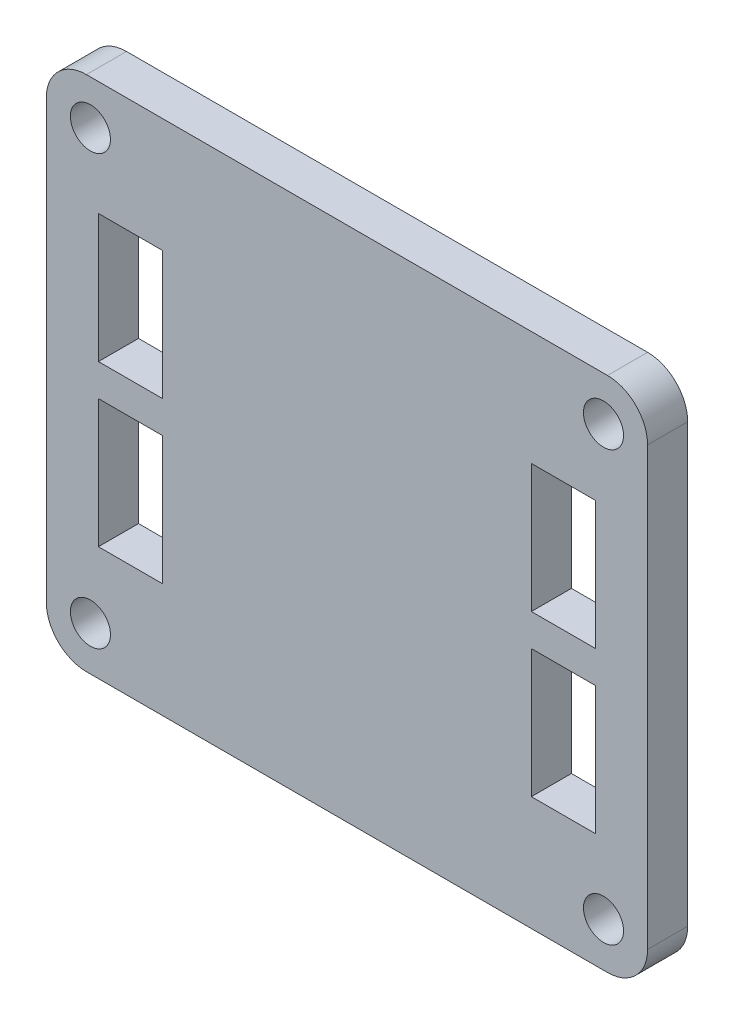
SolidWorks part; units mm, degrees
ref_plane "前基準面" through (0, 0, 0) normal (0, 0, 1) x (1, 0, 0)
ref_plane "上基準面" through (0, 0, 0) normal (0, 1, 0) x (1, 0, 0)
ref_plane "右基準面" through (0, 0, 0) normal (1, 0, 0) x (0, 0, -1)
sketch "草圖1" plane through (0, 0, 0) normal (0, 0, 1) x (1, 0, 0)
  line L1 (37.5, -32.25) -> (-37.5, -32.25)
  line L2 (37.5, -32.25) -> (37.5, 32.25)
  line L3 (37.5, 32.25) -> (-37.5, 32.25)
  line L4 (-37.5, -32.25) -> (-37.5, 32.25)
  line L5 (0, 32.25) -> (0, -32.25) construction
  line L6 (37.5, 0) -> (-37.5, 0) construction
  point P0 (0, 0)
  dimension "D1" = 75
  dimension "D2" = 64.5
extrude "填料-伸長1" add sketch "草圖1" along normal blind 5
sketch "草圖2" plane through (0, 0, 0) normal (1, 0, 0) x (0, 0, -1)
  line L0 (0, 29.8702) -> (0, 0)
  line L4 (33.1041, 21) -> (33.1041, -21)
  line L5 (33.1041, 21) -> (0, 29.8702)
  line L6 (0, 0) -> (0, -29.8702)
  line L7 (33.1041, 0) -> (1.1057, 0) construction
  line L8 (33.1041, -21) -> (0, -29.8702)
extrude "填料-伸長2" add sketch "草圖2" along normal blind 2 and the other way blind 2
sketch "草圖4" plane through (0, 0, 0) normal (0, 0, -1) x (-1, 0, 0)
  line L0 (-37.5, 32.25) -> (37.5, 32.25) construction
  line L1 (37.5, 32.25) -> (37.5, -32.25) construction
  line L2 (0, 32.25) -> (0, -5.7529) construction
  line L3 (-37.5, 0) -> (4.9081, 0) construction
  line L4 (-37.5, -32.25) -> (-37.5, 32.25) construction
  circle A0 centre (32, 26.75) radius 2.5
  circle A1 centre (32, -26.75) radius 2.5
  circle A2 centre (-32, -26.75) radius 2.5
  circle A3 centre (-32, 26.75) radius 2.5
  dimension "D1" = 5
  dimension "D2" = 5.5
  dimension "D3" = 5.5
extrude "除料-伸長2" cut sketch "草圖4" against normal through all
sketch "草圖5" plane through (0, 0, 0) normal (0, 0, -1) x (-1, 0, 0)
  line L0 (-31, 10) -> (-11.6083, 10) construction
  line L1 (-31, 18) -> (-23, 18)
  line L2 (-31, 18) -> (-31, 2)
  line L3 (-31, 2) -> (-23, 2)
  line L4 (-23, 18) -> (-23, 2)
  line L5 (31, 2) -> (23, 2)
  line L6 (-37.5, -32.25) -> (-37.5, 32.25) construction
  line L7 (-46.9143, 0) -> (37.5, 0) construction
  line L8 (37.5, 32.25) -> (37.5, -32.25) construction
  line L9 (0, 29.8702) -> (0, -34.9399) construction
  line L10 (23, 18) -> (23, 2)
  line L11 (2, 29.8702) -> (-2, 29.8702) construction
  line L20 (31, 18) -> (23, 18)
  line L21 (31, 18) -> (31, 2)
  line L22 (31, -18) -> (31, -2)
  line L23 (31, -18) -> (23, -18)
  line L24 (23, -18) -> (23, -2)
  line L25 (31, -2) -> (23, -2)
  line L26 (-31, -2) -> (-23, -2)
  line L27 (-23, -18) -> (-23, -2)
  line L28 (-31, -18) -> (-23, -18)
  line L29 (-31, -18) -> (-31, -2)
  dimension "D1" = 8
  dimension "D2" = 16
  dimension "D3" = 10
  dimension "D4" = 6.5
extrude "除料-伸長3" cut sketch "草圖5" against normal through all
fillet "圓角1" radius 5 6 edges at (37.5, 32.25, 2.5) (-37.5, -32.25, 2.5) (-37.5, 32.25, 2.5) (37.5, -32.25, 2.5) (0, -21, -33.1041) (0, 21, -33.1041)
sketch "草圖6" plane through (2, 0, 0) normal (1, 0, 0) x (0, 0, -1)
  line L1 (0, 29.8702) -> (33.7878, 29.8702)
  line L2 (0, 29.8702) -> (0, -30.7313)
  line L3 (0, -30.7313) -> (33.7878, -30.7313)
  line L4 (33.7878, 29.8702) -> (33.7878, -30.7313)
extrude "除料-伸長4" cut sketch "草圖6" against normal blind 10
